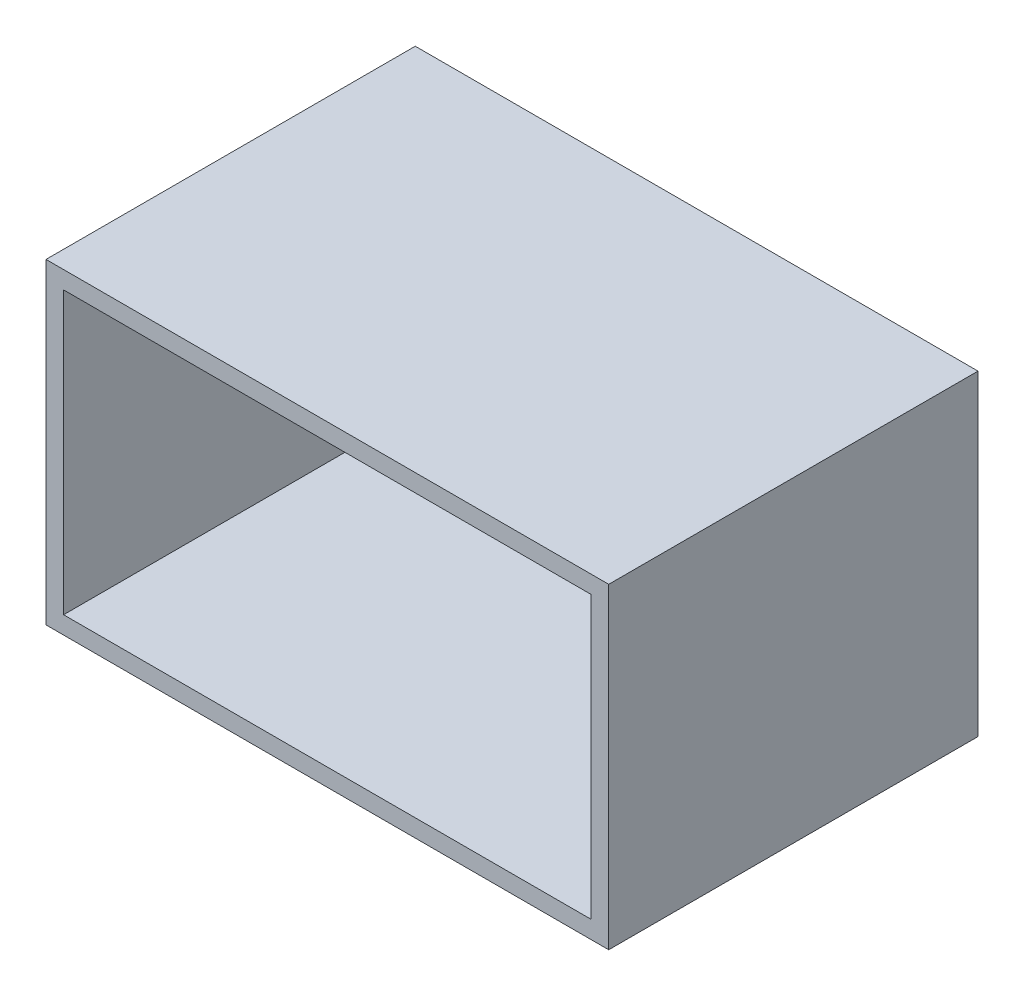
SolidWorks part; units mm, degrees
material "ABS"
ref_plane "前基準面" through (0, 0, 0) normal (0, 0, 1) x (1, 0, 0)
ref_plane "上基準面" through (0, 0, 0) normal (0, 1, 0) x (1, 0, 0)
ref_plane "右基準面" through (0, 0, 0) normal (1, 0, 0) x (0, 0, -1)
sketch "草圖1" plane through (0, 0, 0) normal (0, 0, 1) x (1, 0, 0)
  line L1 (-80, -45) -> (80, -45)
  line L2 (-80, -45) -> (-80, 45)
  line L3 (-80, 45) -> (80, 45)
  line L4 (80, -45) -> (80, 45)
  line L5 (-80, -45) -> (80, 45) construction
  line L6 (-80, 45) -> (80, -45) construction
  point P0 (0, 0)
  dimension "D1" = 160
  dimension "D2" = 90
extrude "填料-伸長1" add sketch "草圖1" along normal blind 105
sketch "草圖2" plane through (0, 0, 105) normal (0, 0, 1) x (1, 0, 0)
  line L8 (75, -40) -> (75, 40)
  line L9 (75, 40) -> (-75, 40)
  line L10 (-75, 40) -> (-75, -40)
  line L11 (-75, -40) -> (75, -40)
  line L12 (75, -40) -> (75, 40)
  line L13 (75, 40) -> (-75, 40)
  line L14 (-75, 40) -> (-75, -40)
  line L15 (-75, -40) -> (75, -40)
  dimension "D1" = 5
extrude "除料-伸長1" cut sketch "草圖2" against normal offset from surface (100 mm away) 5 up to face at (0, 0, 0)
